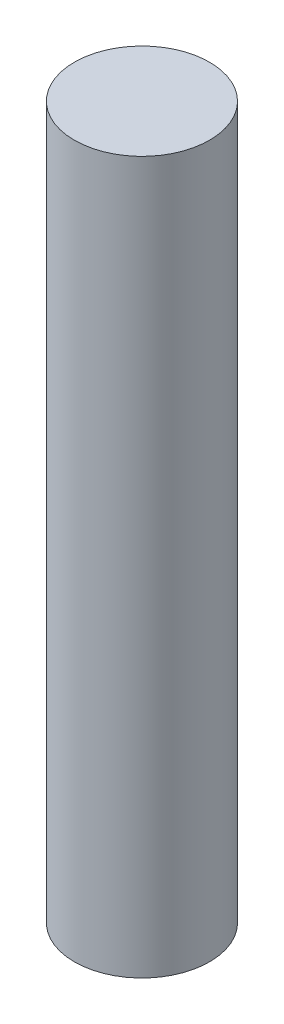
SolidWorks part; units mm, degrees
ref_plane "Front Plane" through (0, 0, 0) normal (0, 0, 1) x (1, 0, 0)
ref_plane "Top Plane" through (0, 0, 0) normal (0, 1, 0) x (1, 0, 0)
ref_plane "Right Plane" through (0, 0, 0) normal (1, 0, 0) x (0, 0, -1)
sketch "Sketch1" plane through (0, 0, 0) normal (0, 1, 0) x (1, 0, 0)
  circle A0 centre (0, 0) radius 0.95
  dimension "D1" = 1.9
extrude "Boss-Extrude1" add sketch "Sketch1" along normal mid plane 10
